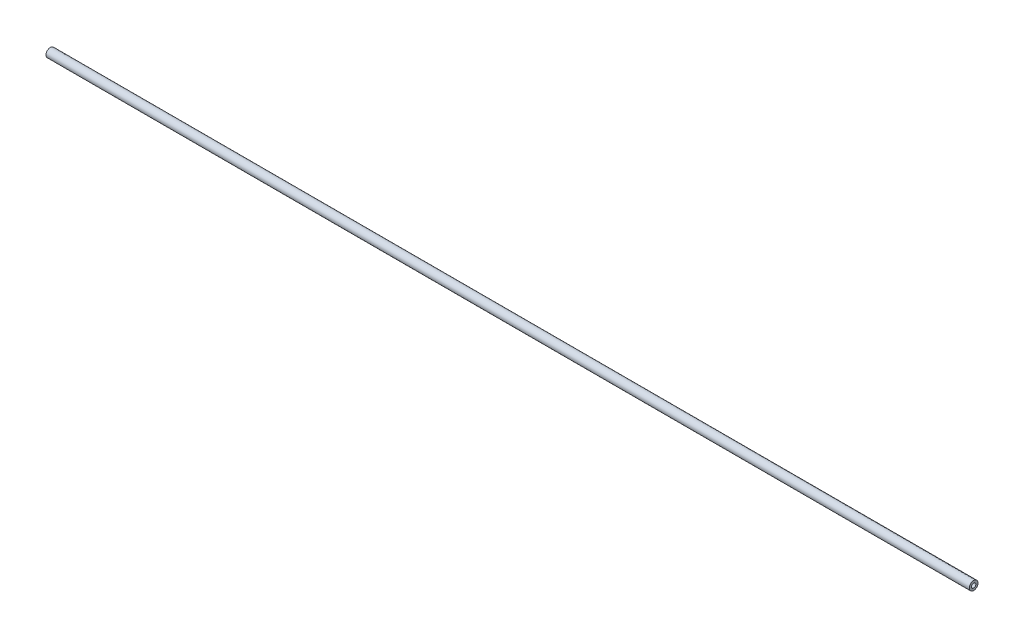
SolidWorks part; units mm, degrees
ref_plane "Front Plane" through (0, 0, 0) normal (0, 0, 1) x (1, 0, 0)
ref_plane "Top Plane" through (0, 0, 0) normal (0, 1, 0) x (1, 0, 0)
ref_plane "Right Plane" through (0, 0, 0) normal (1, 0, 0) x (0, 0, -1)
sketch "Sketch1" plane through (0, 0, 0) normal (1, 0, 0) x (0, 0, -1)
  circle A0 centre (0, 0) radius 3
  circle A1 centre (0, 0) radius 1.5
  dimension "D1" = 6
  dimension "D2" = 3
extrude "Boss-Extrude1" add sketch "Sketch1" along normal mid plane 635
